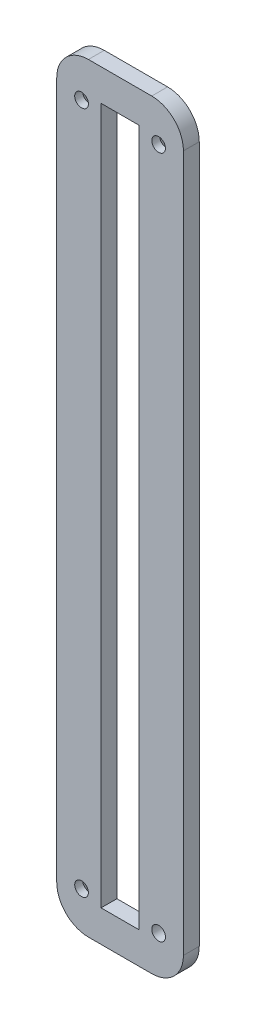
SolidWorks part; units mm, degrees
ref_plane "Front Plane" through (0, 0, 0) normal (0, 0, 1) x (1, 0, 0)
ref_plane "Top Plane" through (0, 0, 0) normal (0, 1, 0) x (1, 0, 0)
ref_plane "Right Plane" through (0, 0, 0) normal (1, 0, 0) x (0, 0, -1)
sketch "Sketch1" plane through (0, 0, 8) normal (0, 0, 1) x (1, 0, 0)
  line L0 (273.05, -152.4) -> (-273.05, -152.4) construction
  line L1 (-31.75, -152.4) -> (-82.55, -152.4)
  line L2 (-31.75, -152.4) -> (-31.75, 152.4)
  line L3 (-31.75, 152.4) -> (-82.55, 152.4)
  line L4 (-82.55, -152.4) -> (-82.55, 152.4)
  line L5 (-31.75, -152.4) -> (-82.55, 152.4)
  line L6 (-31.75, 152.4) -> (-82.55, -152.4)
  line L7 (-69.85, -136.95) -> (-72.6, -136.95) construction
  line L8 (-31.75, -150.9) -> (-31.75, -134.85) construction
  line L9 (-57.15, 0) -> (-82.55, 0)
  line L10 (-49.53, 139.7) -> (-64.77, 139.7)
  line L11 (-49.53, 139.7) -> (-49.53, -139.7)
  line L12 (-49.53, -139.7) -> (-64.77, -139.7)
  line L13 (-64.77, 139.7) -> (-64.77, -139.7)
  line L14 (-49.53, 139.7) -> (-64.77, -139.7)
  line L15 (-49.53, -139.7) -> (-64.77, 139.7)
  line L16 (-72.6, -136.95) -> (-72.6, -139.7) construction
  line L17 (-44.45, -139.7) -> (-44.45, -136.95) construction
  line L18 (-41.7, 136.95) -> (-41.7, 139.7) construction
  circle A0 centre (-69.85, -139.7) radius 12.7
  circle A1 centre (-44.45, -139.7) radius 12.7
  circle A2 centre (-44.45, -139.7) radius 2.75
  circle A3 centre (-69.85, -139.7) radius 2.75
  circle A4 centre (-273.05, -139.7) radius 2.75 construction
  circle A5 centre (-44.45, 139.7) radius 2.75
  circle A6 centre (-69.85, 139.7) radius 2.75
  circle A7 centre (-69.85, 139.7) radius 12.7
  circle A8 centre (-44.45, 139.7) radius 12.7
  circle A9 centre (-72.6, -136.95) radius 2.75
  circle A10 centre (-41.7, -136.95) radius 2.75
  circle A11 centre (-72.6, 136.95) radius 2.75
  circle A12 centre (-72.6, 136.95) radius 2.75
  circle A14 centre (-41.7, 136.95) radius 2.75
  point P4 (-57.15, 0)
  point P28 (-57.15, 0)
  line M50 (-31.75, 139.7) -> (-260.35, 139.7)
  line M54 (-260.35, -139.7) -> (-31.75, -139.7)
  dimension "D1" = 304.8
  dimension "D2" = 15.24
extrude "Boss-Extrude3" add sketch "Sketch1" against normal blind 6.35 contours L6 A8 L2 A1 L5 L11 | L6 A0 L4 L9 L13 | L5 A1 L11 | L13 A0 L6 | A3 A0 L6 M54 | A0 A1 L1 | A2 L5 A1 L12 M54 | A2 A10 L11 A1 L5 M54 | A0 L6 M54 | A1 L5 M54 | A1 L5 M54 | A0 L6 M54 | L4 A7 L5 L13 L9 | L11 A8 L6 | L5 A7 L13 | A7 L10 A6 L5 M50 | A6 A11 L13 A7 L5 M50 | A8 L6 A5 M50 | A5 A12 L6 A8 L11 M50 | A8 L6 M50 | A8 L6 M50 | A7 L5 M50 | A7 L5 M50 | A6 M50 | A5 M50 | A11 A6 M50 | A6 A11 M50 | A12 A5 M50 | A5 A12 M50 | L3 A8 A7 | A3 M54 | A3 A9 L6 A0 L13 M54 | A9 A3 M54 | A3 A9 M54 | A2 M54 | A2 A10 M54 | A10 A2 M54
sketch "Sketch2" plane through (0, 0, 8) normal (0, 0, 1) x (1, 0, 0)
  circle A0 centre (-41.7, 136.95) radius 2.75
  circle A1 centre (-72.6, 136.95) radius 2.75
  circle A2 centre (-41.7, -136.95) radius 2.75
  circle A3 centre (-72.6, -136.95) radius 2.75
  arc A4 (-69.85, -136.95) -> (-72.6, -139.7) centre (-72.6, -136.95) ccw construction
  arc A5 (-72.6, 139.7) -> (-69.85, 136.95) centre (-72.6, 136.95) ccw construction
extrude "Cut-Extrude1" cut sketch "Sketch2" against normal through all
chamfer "Chamfer1" distance 3.175 angle 45 3 edges at (-75.35, -136.95, 1.65) (-75.35, 136.95, 1.65) (-44.45, 136.95, 1.65)
